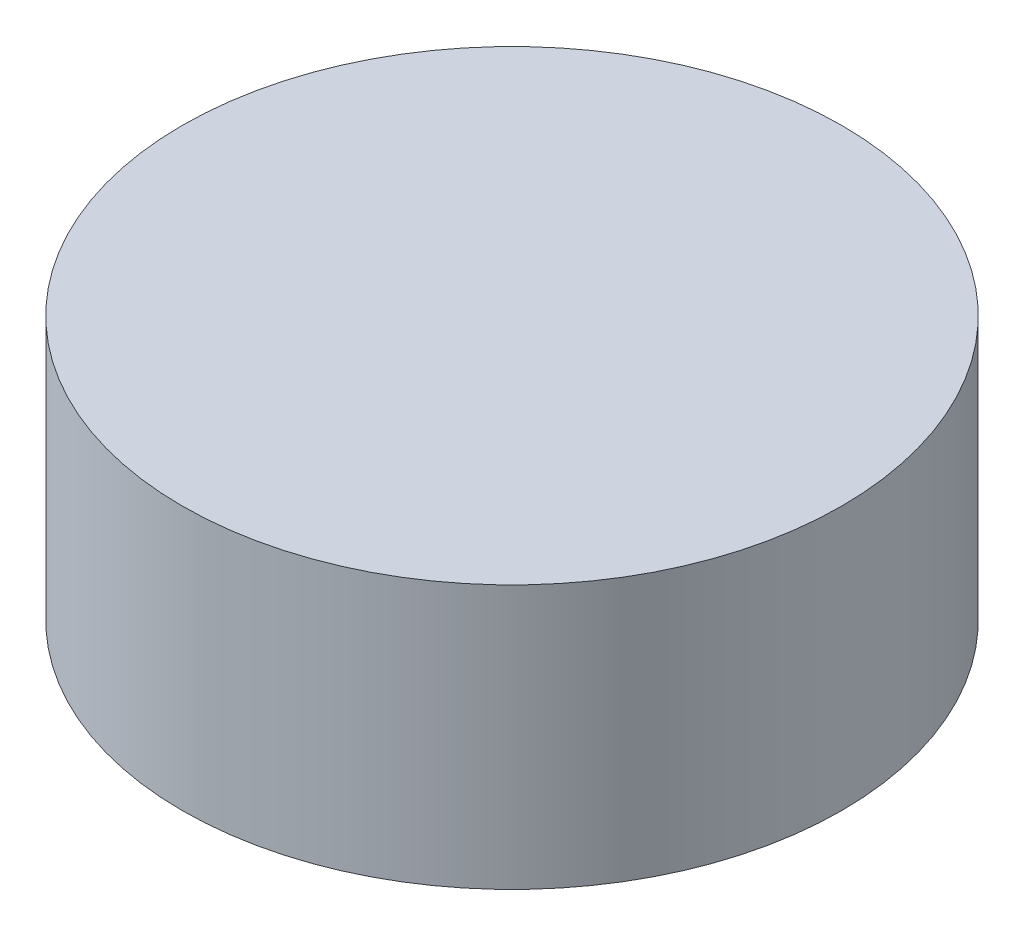
SolidWorks part; units mm, degrees
ref_plane "Front Plane" through (0, 0, 0) normal (0, 0, 1) x (1, 0, 0)
ref_plane "Top Plane" through (0, 0, 0) normal (0, 1, 0) x (1, 0, 0)
ref_plane "Right Plane" through (0, 0, 0) normal (1, 0, 0) x (0, 0, -1)
sketch "Sketch1" plane through (0, 0, 0) normal (0, 1, 0) x (1, 0, 0)
  circle A0 centre (0, 0) radius 125
  dimension "D1" = 250
extrude "Boss-Extrude1" add sketch "Sketch1" along normal mid plane 100
